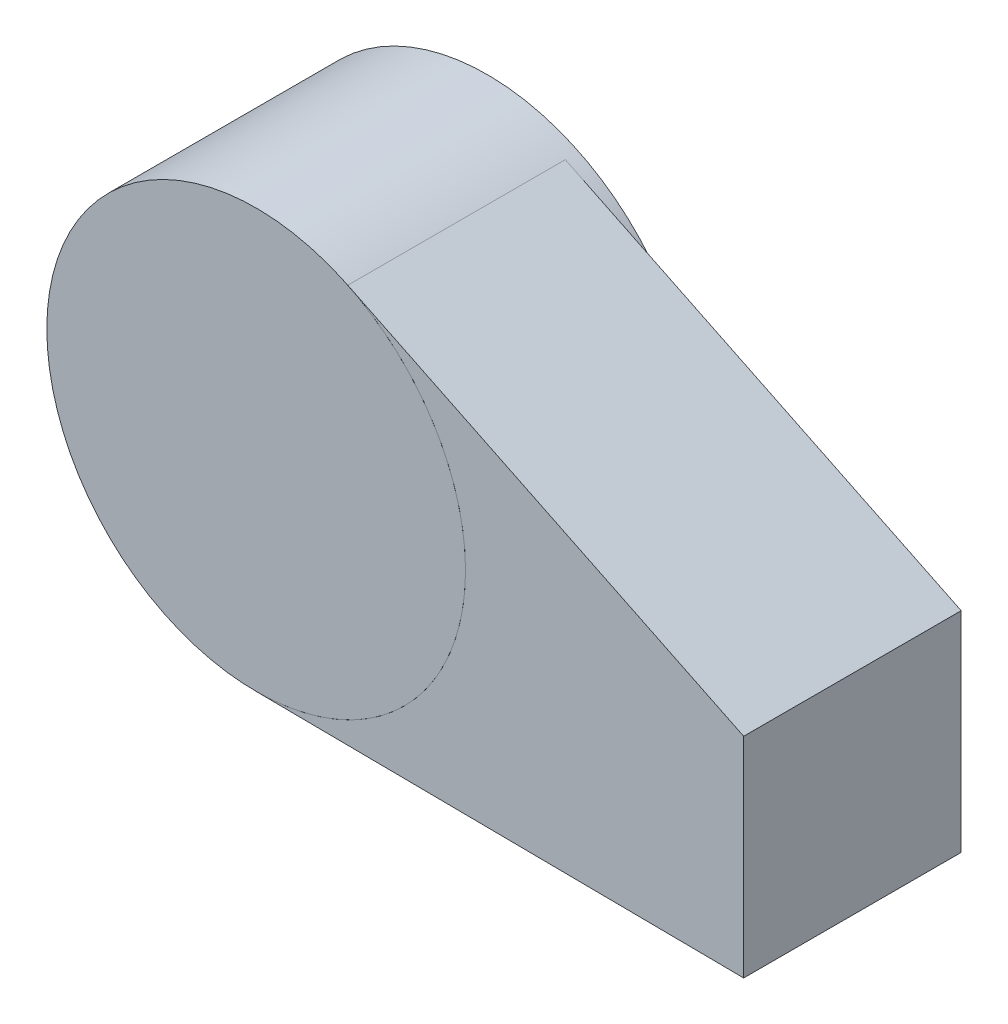
SolidWorks part; units mm, degrees
ref_plane "Front Plane" through (0, 0, 0) normal (0, 0, 1) x (1, 0, 0)
ref_plane "Top Plane" through (0, 0, 0) normal (0, 1, 0) x (1, 0, 0)
ref_plane "Right Plane" through (0, 0, 0) normal (1, 0, 0) x (0, 0, -1)
sketch "Sketch2" plane through (0, 0, 0) normal (0, 0, 1) x (1, 0, 0)
  line L0 (179.3017, -1.6292) -> (33.6963, 69.2356)
  line L1 (179.3017, -78.6292) -> (179.3017, -1.6292)
  line L2 (179.3017, -78.6292) -> (-0.6983, -76.9968)
  circle A0 centre (0, 0) radius 77
  dimension "D1" = 154
  dimension "D3" = 180
extrude "Boss-Extrude3" add sketch "Sketch2" along normal blind 80 contours A0 L2 L1 L0
sketch "Sketch4" plane through (0, 0, 0) normal (0, 0, -1) x (-1, 0, 0)
  circle A0 centre (0, 0) radius 77
extrude "Boss-Extrude4" add sketch "Sketch4" along normal blind 5 and the other way blind 80 separate body
